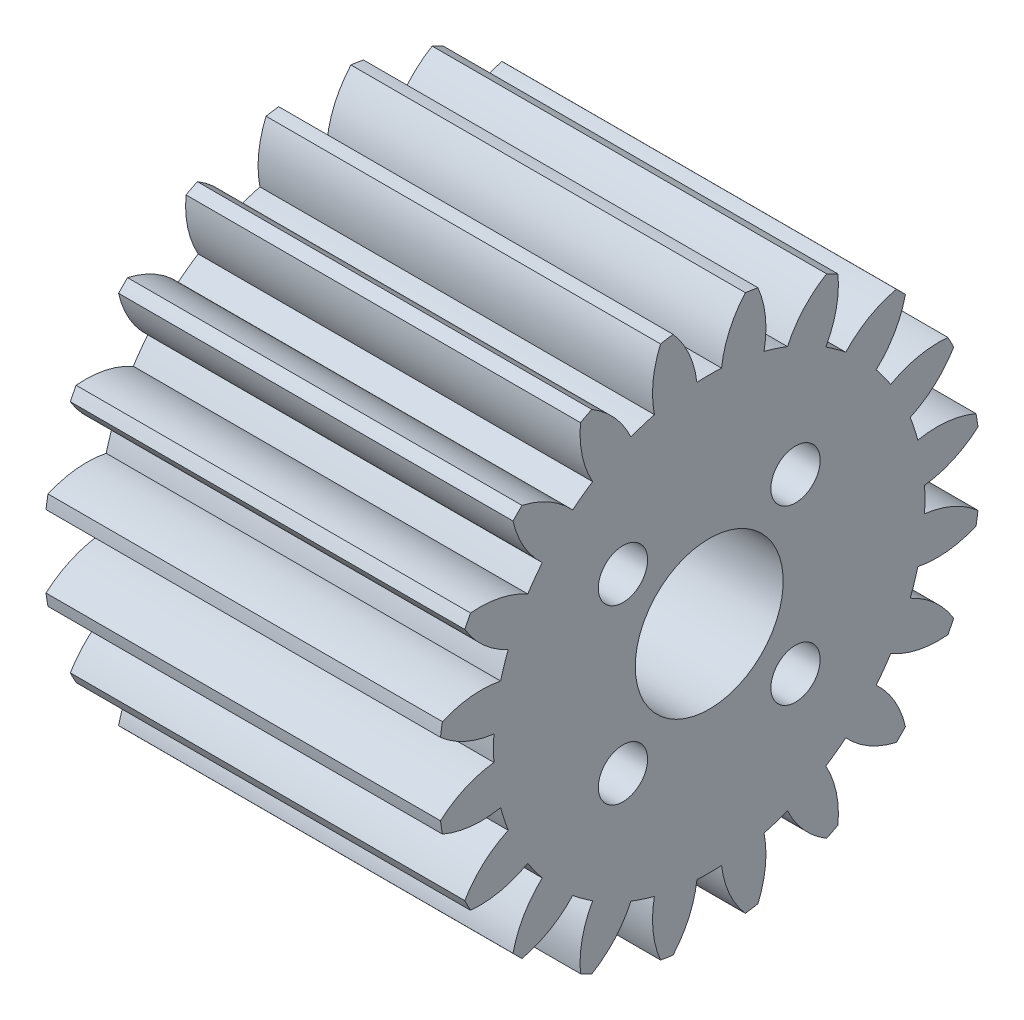
SolidWorks part; units mm, degrees
ref_plane "Plane1" through (0, 0, 0) normal (0, 0, 1) x (1, 0, 0)
ref_plane "Plane2" through (0, 0, 0) normal (0, 1, 0) x (1, 0, 0)
ref_plane "Plane3" through (0, 0, 0) normal (1, 0, 0) x (0, 0, -1)
sketch "HoldingSke" plane through (0, 0, 0) normal (0, 1, 0) x (1, 0, 0)
  line L0 (0, 0) -> (0.9397, -0.342)
  line L1 (-15, 0) -> (100, 0) construction
  line L2 (0, 0) -> (-2.1039, 2.3779)
  line L3 (0, 0) -> (-11.863, 4.5341)
  line L4 (0, 0) -> (8.1152, 2.9537)
  line L5 (0, 0) -> (-46.8476, -17.4728)
  line L6 (0, 0) -> (-6.6317, -4.4744)
  line L7 (-2.1039, 2.3779) -> (8.6586, 51.2059)
  line L8 (-76.2, 54.61) -> (-75.5, 54.61)
  line L9 (-71.009, 38.7566) -> (-53.1078, 45.2721)
  line L10 (-76.2, 71.12) -> (104.1128, 71.12)
  line L11 (0, 0) -> (-8, 0)
  line L12 (-76.2, 101.6) -> (-76.162, 101.6)
  line L13 (24.9733, 27.94) -> (52.9518, 28.4284)
  line L14 (24.9733, 27.94) -> (24.9743, 27.94)
  line L15 (24.9733, 27.94) -> (100.4006, 29.5858)
  line L16 (-63.627, -1) -> (-12.827, -1)
  circle A0 centre (0, 0) radius 2
  circle A1 centre (0, 0) radius 8.749
  circle A2 centre (0, 0) radius 37.5
  circle A3 centre (0, 0) radius 2
  dimension "MHD" = 17.498
  dimension "Hub_dia" = 75
  dimension "Bore" = 4
  dimension "MBD" = 4
  dimension "Num_teeth" = 20
  dimension "Pitch" = 1
  dimension "Overall_len" = 50
  dimension "Show_teeth" = 20
  dimension "Thickness" = 8
  dimension "OAL" = 50.0001
  dimension "T_dim" = 0.7
  dimension "Ap" = 20
  dimension "H" = 19.05
  dimension "Pitch_radius" = 180.3128
  dimension "Width" = 8
  dimension "Backlash" = 0.038
  dimension "Addendum_fac" = 1
  dimension "Dedendum_fac" = 1.25
  dimension "Clearance_fac" = 0.25
  dimension "Dedendum_add" = 0.001
  dimension "Module" = 1
sketch "BasProSke" plane through (0, 0, 0) normal (0, 1, 0) x (1, 0, 0)
  line L0 (-10, 0) -> (60, 0) construction
  line L1 (0, 0) -> (0, 11)
  line L2 (0, 0) -> (16, 0)
  line L3 (16, 0) -> (16, 11)
  line L4 (16, 11) -> (0, 11)
  dimension "Thickness" = 16
  dimension "Diameter" = 22
revolve "Base-Revolve" add sketch "BasProSke" angle 360 about L0
sketch "Sketch1" plane through (16, 0, 0) normal (1, 0, 0) x (0, 0, -1)
  line L0 (0, 0) -> (7.2737, 0)
  line L1 (7.2737, 0) -> (-4.5, 0)
  line L2 (-4.5, 4.5) -> (-4.5, 0)
  line L3 (4.5, 4.5) -> (2.5, 4.5)
  line L4 (4.5, 4.5) -> (4.5, 2.5)
  line L5 (4.5, 2.5) -> (2.5, 2.5)
  line L6 (2.5, 4.5) -> (2.5, 2.5)
  line L7 (4.5, -2.5) -> (2.5, -2.5)
  line L8 (4.5, -2.5) -> (4.5, -4.5)
  line L9 (4.5, -4.5) -> (2.5, -4.5)
  line L10 (2.5, -2.5) -> (2.5, -4.5)
  line L11 (-4.5, 2.5) -> (-2.5, 2.5)
  line L12 (-4.5, 2.5) -> (-4.5, 4.5)
  line L13 (-4.5, 4.5) -> (-2.5, 4.5)
  line L14 (-2.5, 2.5) -> (-2.5, 4.5)
  line L15 (-4.5, -2.5) -> (-2.5, -2.5)
  line L16 (-4.5, -2.5) -> (-4.5, -4.5)
  line L17 (-4.5, -4.5) -> (-2.5, -4.5)
  line L18 (-2.5, -2.5) -> (-2.5, -4.5)
  line L19 (-4.5, 0) -> (-4.5, -4.5)
  circle A0 centre (3.5, 3.5) radius 1
  circle A1 centre (-3.5, 3.5) radius 1
  circle A2 centre (-3.5, -3.5) radius 1
  circle A3 centre (3.5, -3.5) radius 1
  dimension "D21" = 2
  dimension "D22" = 2
  dimension "D23" = 2
  dimension "D24" = 2
  dimension "D1" = 2
  dimension "D2" = 2
  dimension "D3" = 2
  dimension "D4" = 2
  dimension "D5" = 2
  dimension "D6" = 2
  dimension "D7" = 2
  dimension "D8" = 2
  dimension "D9" = 2.5
  dimension "D10" = 2.5
  dimension "D11" = 2.5
  dimension "D12" = 2.5
  dimension "D13" = 5
  dimension "D14" = 5
  dimension "D15" = 2
  dimension "D16" = 2.5
  dimension "D17" = 1
  dimension "D18" = 1
  dimension "D19" = 1
  dimension "D20" = 1
extrude "Cut-Extrude1" cut sketch "Sketch1" against normal blind 30 contours A0 | A1 | A2 | A3
sketch "TooCutSke" plane through (0, 0, 0) normal (1, 0, 0) x (0, 0, -1)
  line L1 (0, 0) -> (0, 107) construction
  line L2 (0, 0) -> (-0.8511, 9.9637) construction
  line L3 (0, 0) -> (-3.1206, 19.7028) construction
  line L4 (-0.8511, 9.9637) -> (-1.5603, 9.8514) construction
  arc A0 (0.4999, 8.7347) -> (-0.4999, 8.7347) centre (0, 0) ccw
  arc A1 (1.4852, 10.9249) -> (-1.4852, 10.9249) centre (0, 0) ccw
  circle A2 centre (0, 0) radius 10 construction
  circle A3 centre (0, 0) radius 9.3969 construction
  arc A4 (-0.4999, 8.7347) -> (-1.4852, 10.9249) centre (-4.4722, 8.2645) ccw
  arc A5 (1.4852, 10.9249) -> (0.4999, 8.7347) centre (4.4722, 8.2645) ccw
  dimension "Root_dia" = 17.498
  dimension "Overcut_dia" = 22.0508
  dimension "Pitch_dia" = 20
  dimension "Base_dia" = 18.7939
  dimension "Flank_rad" = 4
  dimension "Half_ang" = 9
  dimension "Half_CT" = 0.7181
extrude "ToothCut" cut sketch "TooCutSke" along normal through all
fillet "Breaks" [suppressed] radius 0.02
fillet "RootFillets" [suppressed] radius 0.251
pattern_circular "TeethCuts" count 20 every 18 about axis through (-10, 0, 0) along (1, 0, 0) of "ToothCut", "RootFillets", "Breaks"
sketch "HubNeaOneSke" plane through (0, 0, 0) normal (-1, 0, 0) x (0, 0, 1)
  circle A0 centre (0, 0) radius 8.749
  dimension "Diameter" = 17.498
extrude "HubNearOne" [suppressed] add sketch "HubNeaOneSke" along normal blind 34.0001
sketch "HubNeaBotSke" plane through (0, 0, 0) normal (-1, 0, 0) x (0, 0, 1)
  circle A0 centre (0, 0) radius 8.749
  dimension "Diameter" = 17.498
extrude "HubNearBoth" [suppressed] add sketch "HubNeaBotSke" along normal blind 17
ref_plane "FarPln" through (16, 0, 0) normal (1, 0, 0) x (0, 0, -1)
sketch "HubFarSke" plane through (16, 0, 0) normal (1, 0, 0) x (0, 0, -1)
  circle A0 centre (0, 0) radius 8.749
  dimension "Diameter" = 17.498
extrude "HubFar" [suppressed] add sketch "HubFarSke" along normal blind 17
sketch "BorSke" plane through (0, 0, 0) normal (1, 0, 0) x (0, 0, -1)
  circle A0 centre (0, 0) radius 3
  dimension "Diameter" = 6
extrude "Bore" cut sketch "BorSke" along normal mid plane 100.0001
sketch "KeySke" plane through (0, 0, 0) normal (1, 0, 0) x (0, 0, -1)
  line L0 (-0.8, 0) -> (-0.8, 2.7)
  line L1 (-0.8, 2.7) -> (0.8, 2.7)
  line L2 (0.8, 2.7) -> (0.8, 0)
  line L3 (0, 0) -> (0, 34) construction
  line L4 (-0.8, 0) -> (0.8, 0)
  dimension "Offset" = 2.7
  dimension "Width" = 1.6
extrude "Keyway" [suppressed] cut sketch "KeySke" along normal mid plane 100.0001
pattern_circular "Keyway2" [suppressed] count 2 every 90 about axis through (-10, 0, 0) along (1, 0, 0)
equation "' \"Module@HoldingSke\" = 6.35"
equation "' \"Num_teeth@HoldingSke\" = 12"
equation "' \"Ap@HoldingSke\" =  20"
equation "' \"Ap@HoldingSke\" = 20"
equation "' \"Width@HoldingSke\" = 0.5 * 25.4"
equation "' \"Hub_dia@HoldingSke\"= 1 * 25.4"
equation "' \"Hub_dia@HoldingSke\" = 1 * 25.4"
equation "' \"Overall_len@HoldingSke\" = 1.0 * 25.4"
equation "' \"Bore@HoldingSke\" = 0.75 * 25.4"
equation "' \"T_dim@HoldingSke\" = 0.1 * 25.4"
equation "' \"Width@KeySke\" = 0.25 * 25.4"
equation "' \"Show_teeth@HoldingSke\" = 13"
equation "' \"Backlash@HoldingSke\" = 0.009 * 25.4"
equation "' \"Addendum_fac@HoldingSke\" = 1.0"
equation "' \"Dedendum_fac@HoldingSke\" = 1.25"
equation "' \"Dedendum_add@HoldingSke\" = 0.00005 * 25.4"
equation "' \"Clearance_fac@HoldingSke\" = 0.25"
equation "\"Pitch@HoldingSke\" = 1 / \"Module@HoldingSke\""
equation "\"Overcut_dia@TooCutSke\" = (\"Num_teeth@HoldingSke\" + 2 * \"Addendum_fac@HoldingSke\") / \"Pitch@HoldingSke\" + 0.002 * 25.4"
equation "\"Pitch_dia@TooCutSke\" = \"Num_teeth@HoldingSke\" / \"Pitch@HoldingSke\""
equation "\"Base_dia@TooCutSke\" = \"Num_teeth@HoldingSke\" / \"Pitch@HoldingSke\" * cos((\"Ap@HoldingSke\"  * 3.14159265 / 180))"
equation "\"Root_dia@TooCutSke\" = (\"Num_teeth@HoldingSke\" + 2) / \"Pitch@HoldingSke\" - 2 * (\"Addendum_fac@HoldingSke\" + \"Dedendum_fac@HoldingSke\") / \"Pitch@HoldingSke\" - \"Dedendum_add@HoldingSke\" * 2"
equation "\"Half_ang@TooCutSke\" = 180 / \"Num_teeth@HoldingSke\""
equation "\"Half_CT@TooCutSke\" = \"Num_teeth@HoldingSke\" / \"Pitch@HoldingSke\" * sin((3.14159265 / 2 / \"Num_teeth@HoldingSke\")) / 2 - 7 * \"Backlash@HoldingSke\" / 4"
equation "\"Flank_rad@TooCutSke\" = \"Num_teeth@HoldingSke\" / \"Pitch@HoldingSke\" / 5"
equation "\"Radius@RootFillets\" = \"Clearance_fac@HoldingSke\" / \"Pitch@HoldingSke\" + \"Dedendum_add@HoldingSke\""
equation "\"Break_rad@Breaks\" = 0.02 / \"Pitch@HoldingSke\""
equation "\"Thickness@HoldingSke\" = \"Width@HoldingSke\""
equation "\"OAL@HoldingSke\" = \"Thickness@HoldingSke\""
equation "\"MHD@HoldingSke\" = (\"Num_teeth@HoldingSke\" + 2) / \"Pitch@HoldingSke\" - 2 * (\"Addendum_fac@HoldingSke\" + \"Dedendum_fac@HoldingSke\")  / \"Pitch@HoldingSke\" - \"Dedendum_add@HoldingSke\" * 2"
equation "\"MBD@HoldingSke\" = (\"Num_teeth@HoldingSke\" + 2) / \"Pitch@HoldingSke\" - 2 * (\"Addendum_fac@HoldingSke\" + \"Dedendum_fac@HoldingSke\")  / \"Pitch@HoldingSke\" - \"Dedendum_add@HoldingSke\" * 2 - 0.002 * 25.4"
equation "\"MHD@HoldingSke\" = ((sgn( \"MHD@HoldingSke\" - \"Hub_dia@HoldingSke\" )-1)*( \"MHD@HoldingSke\" - \"Hub_dia@HoldingSke\" ))/-2+ \"Hub_dia@HoldingSke\""
equation "\"MBD@HoldingSke\" = ((sgn( \"MBD@HoldingSke\" - \"Bore@HoldingSke\" )-1)*( \"MBD@HoldingSke\" - \"Bore@HoldingSke\" ))/-2+ \"Bore@HoldingSke\""
equation "\"OAL@HoldingSke\" = ((sgn( \"OAL@HoldingSke\" - \"Overall_len@HoldingSke\" )+1)*( \"OAL@HoldingSke\" - \"Overall_len@HoldingSke\" ))/2 + \"Overall_len@HoldingSke\" + 0.000002 * 25.4"
equation "\"Num_teeth@TeethCuts\" = int( \"Show_teeth@HoldingSke\" ) + 1"
equation "\"Num_teeth@TeethCuts\" = ((sgn( \"Num_teeth@TeethCuts\" - \"Num_teeth@HoldingSke\" )-1)*( \"Num_teeth@TeethCuts\" - \"Num_teeth@HoldingSke\" ))/-2+ \"Num_teeth@HoldingSke\""
equation "\"Num_teeth@TeethCuts\" = ((sgn( \"Num_teeth@TeethCuts\" - 2.0)+1)*( \"Num_teeth@TeethCuts\" - 2.0))/2 +2.0"
equation "\"Angle@TeethCuts\" = 360.0 / \"Num_teeth@HoldingSke\""
equation "\"Diameter@BasProSke\" = (\"Num_teeth@HoldingSke\" + 2 * \"Addendum_fac@HoldingSke\") / \"Pitch@HoldingSke\""
equation "' \"Fillet_rad@BasProSke\" =  \"Thickness@HoldingSke\" * 0.05"
equation "' \"Fillet_rad@BasProSke\" = \"Thickness@HoldingSke\" * 0.05"
equation "\"MHD@HoldingSke\" = ((sgn( \"MHD@HoldingSke\" - \"Root_dia@TooCutSke\" )-1)*( \"MHD@HoldingSke\" - \"Root_dia@TooCutSke\" ))/-2+ \"Root_dia@TooCutSke\""
equation "\"Diameter@HubNeaOneSke\" = \"MHD@HoldingSke\""
equation "\"Length@HubNearOne\" = \"OAL@HoldingSke\" - \"Thickness@BasProSke\""
equation "\"Diameter@HubNeaBotSke\" = \"MHD@HoldingSke\""
equation "\"Length@HubNearBoth\" = ( \"OAL@HoldingSke\" - \"Thickness@BasProSke\" ) / 2.0"
equation "\"Thickness@FarPln\" = \"Thickness@BasProSke\""
equation "\"Diameter@HubFarSke\" = \"MHD@HoldingSke\""
equation "\"Length@HubFar\" = ( \"OAL@HoldingSke\" - \"Thickness@BasProSke\" ) / 2.0"
equation "\"D1@Bore\" = \"OAL@HoldingSke\" * 2.0"
equation "\"D1@Keyway\" = \"OAL@HoldingSke\" * 2.0"
equation "\"Offset@KeySke\" = \"T_dim@HoldingSke\" + \"MBD@HoldingSke\" / 2.0"
